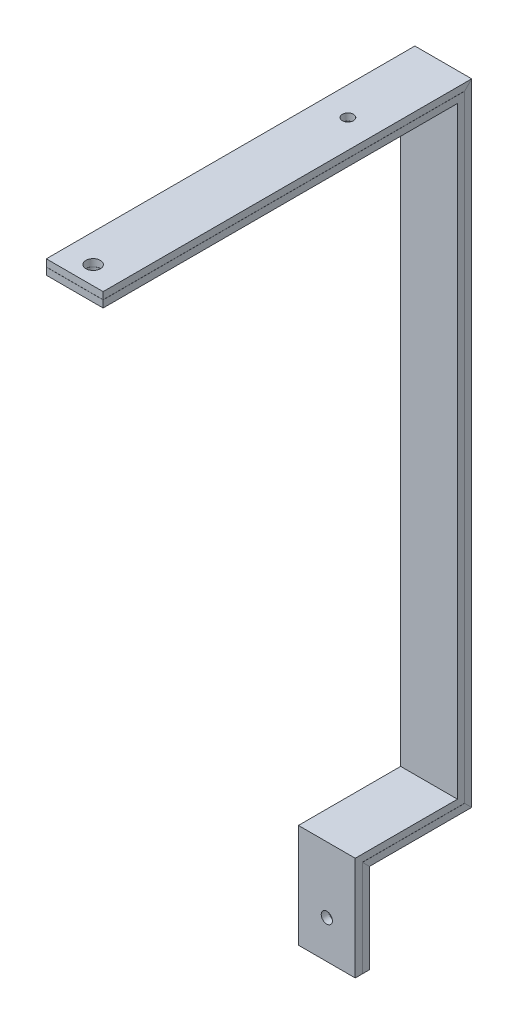
SolidWorks part; units mm, degrees
ref_plane "Alzado" through (0, 0, 0) normal (0, 0, 1) x (1, 0, 0)
ref_plane "Planta" through (0, 0, 0) normal (0, 1, 0) x (1, 0, 0)
ref_plane "Vista lateral" through (0, 0, 0) normal (1, 0, 0) x (0, 0, -1)
sketch "Croquis1" plane through (0, 0, 0) normal (0, 0, 1) x (1, 0, 0)
  line L1 (-25.4, 3.155) -> (25.4, 3.155)
  line L2 (-25.4, 3.155) -> (-25.4, -3.155)
  line L3 (-25.4, -3.155) -> (25.4, -3.155)
  line L4 (25.4, 3.155) -> (25.4, -3.155)
  line L5 (-25.4, 3.155) -> (25.4, -3.155) construction
  line L6 (-25.4, -3.155) -> (25.4, 3.155) construction
  point P0 (0, 0)
  dimension "D1" = 50.8
  dimension "D2" = 6.31
sketch3d "Croquis3D1"
  line L0 (0, 0, 0) -> (0, 0, -326.34)
  line L1 (0, 0, -326.34) -> (0, -557.76, -326.34)
  line L2 (0, -557.76, -326.34) -> (0, -557.76, -234.9362)
  line L3 (0, -557.76, -234.9362) -> (0, -640.92, -234.9362)
  dimension "D1" = 326.34
  dimension "D2" = 557.76
  dimension "D3" = 91.4038
  dimension "D4" = 83.16
sweep "Barrer1" add profiles "Croquis1" path "Croquis3D1"
sketch "Croquis2" plane through (25.4, 0, 0) normal (1, 0, 0) x (0, 0, -1)
  line L0 (0, -3.555) -> (0, -3.255) construction
  line L1 (0, 3.155) -> (0, -3.155) construction
  line L2 (0, 3.155) -> (0, -3.155) construction
  line L3 (0, -3.255) -> (323.085, -3.255)
  line L4 (323.085, -3.255) -> (323.085, -554.505)
  line L5 (323.085, -554.505) -> (231.6812, -554.505)
  line L6 (231.6812, -554.505) -> (231.6812, -640.92)
  line L7 (323.185, -3.155) -> (323.185, -554.605) construction
  line L8 (323.185, -554.605) -> (231.7812, -554.605) construction
  line L9 (231.7812, -554.605) -> (231.7812, -640.92) construction
  line L10 (0, -9.565) -> (316.775, -9.565)
  line L11 (316.775, -9.565) -> (316.775, -548.195)
  line L12 (316.775, -548.195) -> (225.3712, -548.195)
  line L13 (225.3712, -548.195) -> (225.3712, -640.92)
  line L14 (0, -3.255) -> (0, -9.565)
  line L16 (231.6812, -554.505) -> (231.6812, -620.8268) construction
  line L17 (231.7812, -640.92) -> (225.3712, -640.92) construction
  line L18 (225.3712, -548.195) -> (225.3712, -620.8268) construction
  line L19 (225.3712, -640.92) -> (231.6812, -640.92)
  line L20 (0, -3.155) -> (323.185, -3.155) construction
  dimension "D1" = 0.1
  dimension "D2" = 0.1
  dimension "D3" = 0.1
  dimension "D4" = 0.1
  dimension "D5" = 6.31
extrude "Saliente-Extruir1" add sketch "Croquis2" against normal blind 50.8 separate body
sketch "Croquis4" plane through (0, 3.155, 0) normal (0, 1, 0) x (1, 0, 0)
  line L0 (0, 329.495) -> (0, 286.895) construction
  line L1 (-25.4, 329.495) -> (25.4, 329.495) construction
  line L2 (0, 286.895) -> (0, 244.195) construction
  line L3 (0, 244.195) -> (0, 221.195) construction
  circle A0 centre (0, 286.895) radius 3.5 construction
  circle A1 centre (0, 244.195) radius 5
  circle A2 centre (0, 221.195) radius 3.5 construction
  dimension "D4" = 10
  dimension "D5" = 7
  dimension "D6" = 7
  dimension "D1" = 85.3
  dimension "D3" = 23
extrude "Cortar-Extruir2" cut sketch "Croquis4" against normal blind 40
sketch "Croquis6" plane through (0, 3.155, 0) normal (0, 1, 0) x (1, 0, 0)
  line L0 (0, 0) -> (0, 16.5) construction
  circle A0 centre (0, 16.5) radius 6.5
  dimension "D1" = 13
extrude "Cortar-Extruir4" cut sketch "Croquis6" against normal blind 50
sketch "Croquis7" plane through (0, 0, -225.3712) normal (0, 0, 1) x (1, 0, 0)
  line L0 (0, -640.92) -> (0, -606.92) construction
  line L1 (-25.4, -640.92) -> (25.4, -640.92) construction
  circle A0 centre (0, -606.92) radius 5
  dimension "D2" = 10
  dimension "D1" = 34
extrude "Cortar-Extruir5" cut sketch "Croquis7" against normal blind 26
